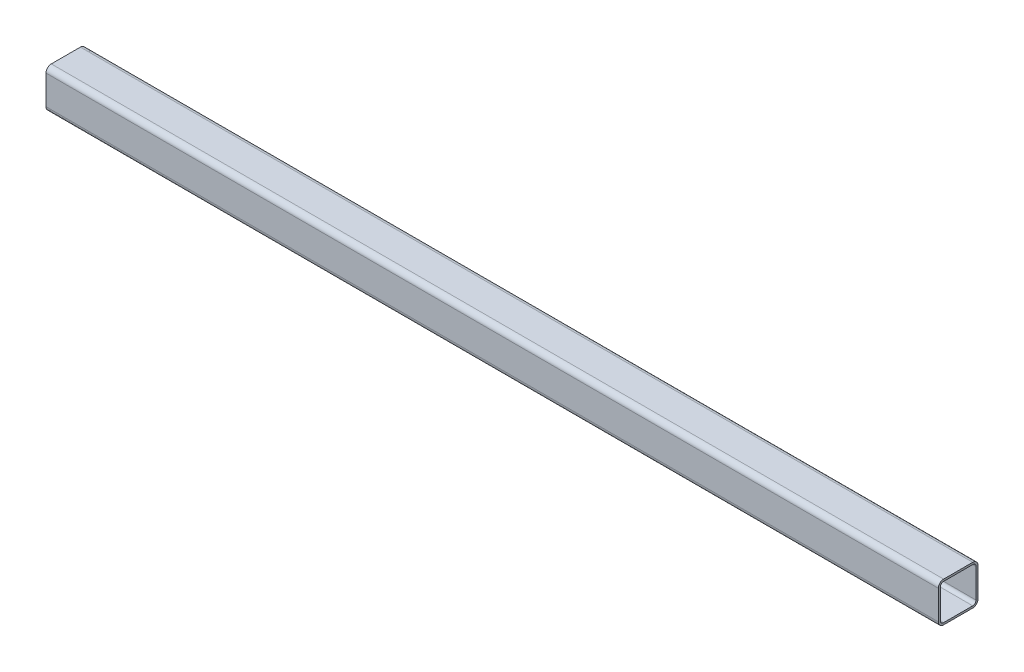
SolidWorks part; units mm, degrees
ref_plane "Front Plane" through (0, 0, 0) normal (0, 0, 1) x (1, 0, 0)
ref_plane "Top Plane" through (0, 0, 0) normal (0, 1, 0) x (1, 0, 0)
ref_plane "Right Plane" through (0, 0, 0) normal (1, 0, 0) x (0, 0, -1)
sketch "Sketch1" plane through (0, 0, 0) normal (1, 0, 0) x (0, 0, -1)
  line L1 (-22, -27) -> (22, -27)
  line L2 (-27, -22) -> (-27, 22)
  line L3 (-22, 27) -> (22, 27)
  line L4 (27, -22) -> (27, 22)
  line L5 (-27, -27) -> (27, 27) construction
  line L6 (-27, 27) -> (27, -27) construction
  arc A0 (-27, -22) -> (-22, -27) centre (-22, -22) ccw
  arc A1 (22, -27) -> (27, -22) centre (22, -22) ccw
  arc A2 (27, 22) -> (22, 27) centre (22, 22) ccw
  arc A3 (-22, 27) -> (-27, 22) centre (-22, 22) ccw
  point P0 (0, 0)
  dimension "D3" = 5
  dimension "D1" = 54
  dimension "D2" = 54
extrude "Extrude-Thin1" add sketch "Sketch1" along normal blind 675 and the other way blind 675 thin
sketch "Sketch3" plane through (0, 0, 0) normal (0, 1, 0) x (1, 0, 0)
  line L0 (0, -25.3) -> (0, 25.3) construction
  circle A0 centre (-387.5, 0) radius 5
  circle A1 centre (-312.5, 0) radius 5
  circle A2 centre (387.5, 0) radius 5
  circle A3 centre (312.5, 0) radius 5
  dimension "D1" = 10
  dimension "D2" = 312.5
  dimension "D3" = 75
extrude "Cut-Extrude1" [suppressed] cut sketch "Sketch3" against normal through all both and the other way through all
